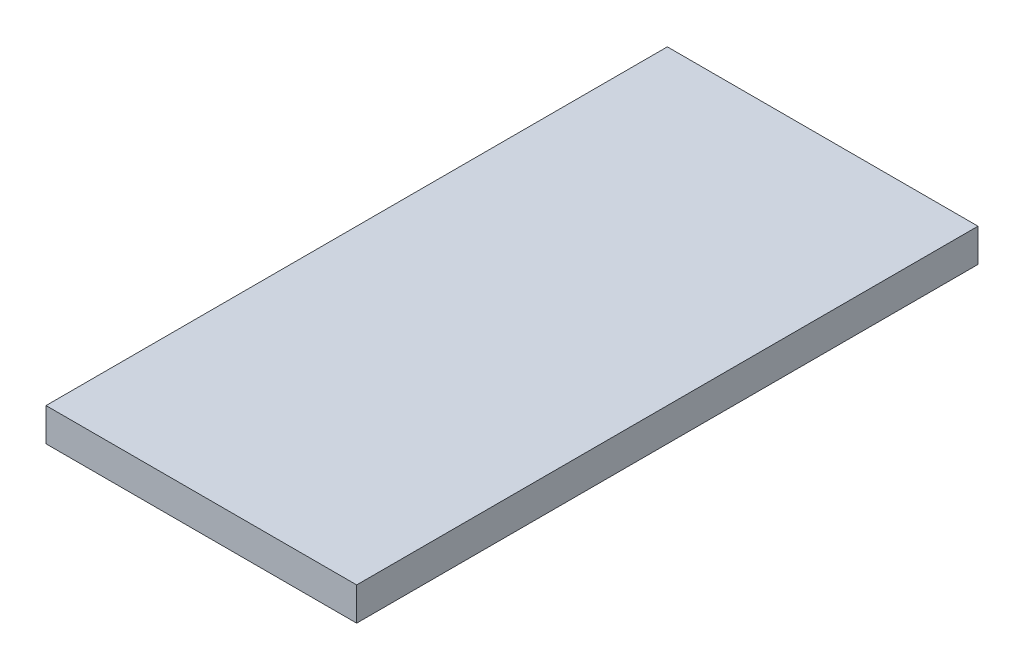
SolidWorks part; units mm, degrees
ref_plane "Front Plane" through (0, 0, 0) normal (0, 0, 1) x (1, 0, 0)
ref_plane "Top Plane" through (0, 0, 0) normal (0, 1, 0) x (1, 0, 0)
ref_plane "Right Plane" through (0, 0, 0) normal (1, 0, 0) x (0, 0, -1)
sketch "Sketch1" plane through (0, 0, 0) normal (0, 1, 0) x (1, 0, 0)
  line L1 (0, 0) -> (15, 0)
  line L2 (0, 0) -> (0, 30)
  line L3 (0, 30) -> (15, 30)
  line L4 (15, 0) -> (15, 30)
  dimension "D1" = 15
  dimension "D2" = 30
extrude "Boss-Extrude1" add sketch "Sketch1" along normal blind 1.6
